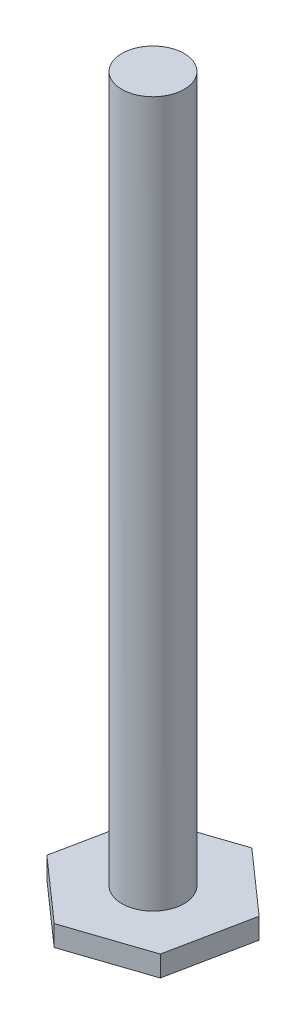
SolidWorks part; units mm, degrees
ref_plane "Front Plane" through (0, 0, 0) normal (0, 0, 1) x (1, 0, 0)
ref_plane "Top Plane" through (0, 0, 0) normal (0, 1, 0) x (1, 0, 0)
ref_plane "Right Plane" through (0, 0, 0) normal (1, 0, 0) x (0, 0, -1)
sketch "Sketch1" plane through (0, 0, 0) normal (0, 0, 1) x (1, 0, 0)
  line L0 (0, 35) -> (1.5, 35)
  line L1 (1.5, 35) -> (1.5, 0)
  line L2 (1.5, 0) -> (0, 0)
  line L3 (0, 0) -> (0, 35)
  dimension "D1" = 1.5
  dimension "D2" = 35
revolve "Revolve1" add sketch "Sketch1" angle 360 about L3
cosmetic thread "Cosmetic Thread1" parameters "D1"=5, "D2"=2.459
sketch "Sketch2" plane through (0, 0, 0) normal (0, 1, 0) x (1, 0, 0)
  line L1 (3.8317, 1.285) -> (0.803, 3.9609)
  line L2 (0.803, 3.9609) -> (-3.0287, 2.6758)
  line L3 (-3.0287, 2.6758) -> (-3.8317, -1.285)
  line L4 (-3.8317, -1.285) -> (-0.803, -3.9609)
  line L5 (-0.803, -3.9609) -> (3.0287, -2.6758)
  line L6 (3.0287, -2.6758) -> (3.8317, 1.285)
  circle A0 centre (0, 0) radius 3.5 construction
  dimension "D1" = 7
extrude "Boss-Extrude1" add sketch "Sketch2" along normal blind 1
